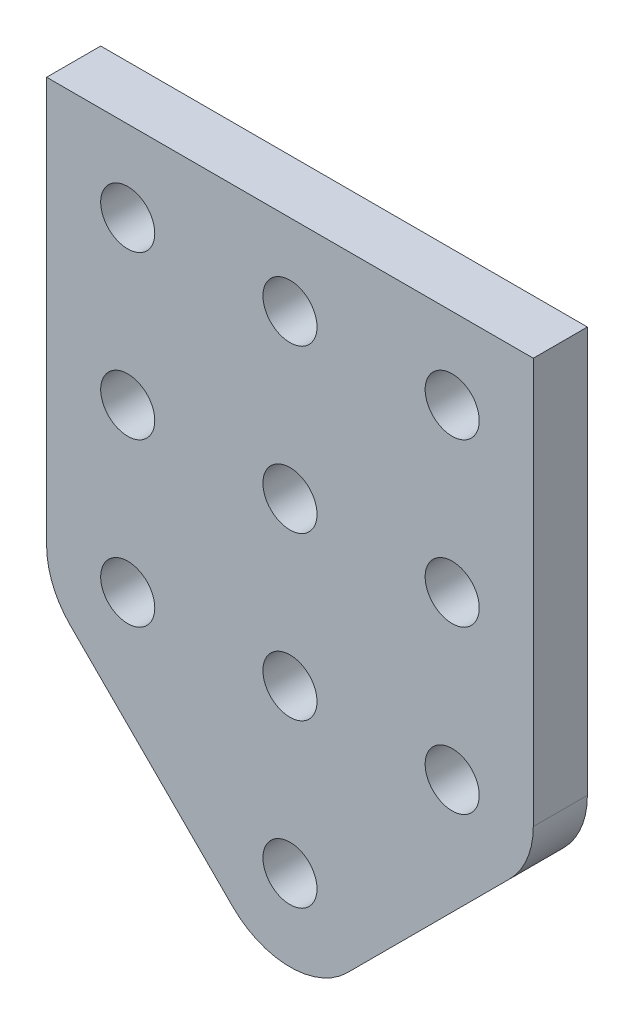
SolidWorks part; units mm, degrees
ref_plane "Alzado" through (0, 0, 0) normal (0, 0, 1) x (1, 0, 0)
ref_plane "Planta" through (0, 0, 0) normal (0, 1, 0) x (1, 0, 0)
ref_plane "Vista lateral" through (0, 0, 0) normal (1, 0, 0) x (0, 0, -1)
sketch "Model" plane through (0, 0, 0) normal (0, 0, 1) x (1, 0, 0)
  line L0 (174.2271, 213.1787) -> (174.2271, 204.1787)
  line L1 (201.2271, 226.6787) -> (174.2271, 226.6787)
  line L2 (174.2271, 213.1787) -> (174.2271, 226.6787)
  line L3 (201.2271, 226.6787) -> (201.2271, 204.1787)
  line L4 (190.909, 191.9967) -> (199.909, 200.9967)
  line L5 (184.5451, 191.9967) -> (175.5451, 200.9967)
  circle A0 centre (187.7271, 204.1787) radius 1.5
  circle A1 centre (178.7271, 204.1787) radius 1.5
  circle A2 centre (187.7271, 213.1787) radius 1.5
  circle A3 centre (178.7271, 213.1787) radius 1.5
  circle A4 centre (196.7271, 213.1787) radius 1.5
  circle A5 centre (187.7271, 195.1787) radius 1.5
  circle A6 centre (196.7271, 204.1787) radius 1.5
  arc A7 (184.5451, 191.9967) -> (190.909, 191.9967) centre (187.7271, 195.1787) ccw
  arc A8 (199.909, 200.9967) -> (201.2271, 204.1787) centre (196.7271, 204.1787) ccw
  arc A9 (174.2271, 204.1787) -> (175.5451, 200.9967) centre (178.7271, 204.1787) ccw
  circle A10 centre (187.7271, 222.1787) radius 1.5
  circle A11 centre (178.7271, 222.1787) radius 1.5
  circle A12 centre (196.7271, 222.1787) radius 1.5
extrude "Saliente-Extruir1" add sketch "Model" along normal blind 3
